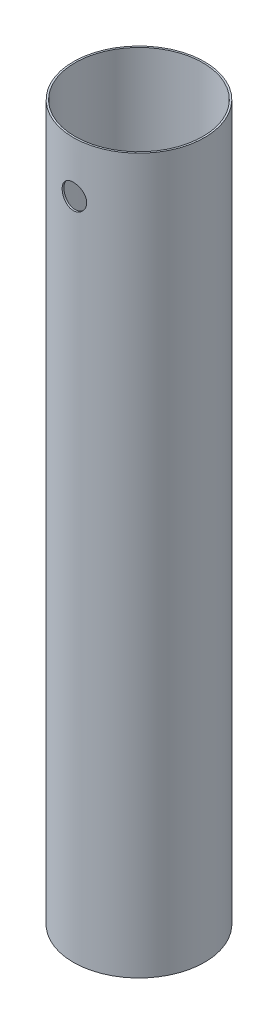
SolidWorks part; units mm, degrees
material "PVC Rígido"
ref_plane "Alzado" through (0, 0, 0) normal (0, 0, 1) x (1, 0, 0)
ref_plane "Planta" through (0, 0, 0) normal (0, 1, 0) x (1, 0, 0)
ref_plane "Vista lateral" through (0, 0, 0) normal (1, 0, 0) x (0, 0, -1)
sketch "Croquis1" plane through (0, 0, 0) normal (0, 1, 0) x (1, 0, 0)
  circle A0 centre (0, 0) radius 55.5
  circle A1 centre (0, 0) radius 57
  dimension "D1" = 111
  dimension "D2" = 114
extrude "Saliente-Extruir1" add sketch "Croquis1" along normal blind 620
ref_plane "Plano1" through (0, 0, 57) normal (0, 0, 1) x (1, 0, 0)
sketch "Croquis2" plane through (0, 0, 57) normal (0, 0, 1) x (1, 0, 0)
  circle A0 centre (0, 575.7415) radius 10.65
  dimension "D1" = 21.3
extrude "Cortar-Extruir1" cut sketch "Croquis2" against normal blind 10
